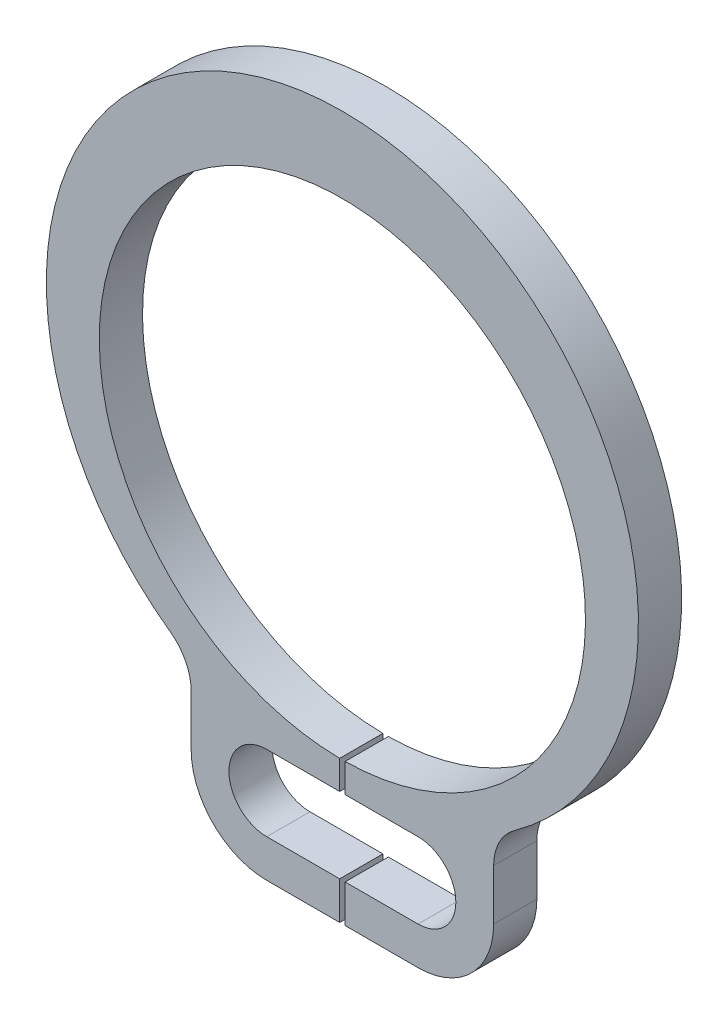
SolidWorks part; units mm, degrees
material "不锈钢 (铁素体)"
ref_plane "前视基准面" through (0, 0, 0) normal (0, 0, 1) x (1, 0, 0)
ref_plane "上视基准面" through (0, 0, 0) normal (0, 1, 0) x (1, 0, 0)
ref_plane "右视基准面" through (0, 0, 0) normal (1, 0, 0) x (0, 0, -1)
sketch "草图1" plane through (0, 0, 0) normal (0, 0, 1) x (1, 0, 0)
  line L0 (0, 1.0126) -> (0, -2.147) construction
  line L1 (-0.7, -3.5657) -> (0.7, -3.5657)
  line L2 (-1.4, -2.8657) -> (-1.4, -2.1453)
  line L3 (1.4, -2.8657) -> (1.4, -2.1453)
  circle A0 centre (0, 0) radius 2.25
  arc A1 (1.4, -2.1453) -> (-1.4, -2.1453) centre (0, 0.21) ccw
  circle A2 centre (-0.7, -2.8657) radius 0.35
  circle A4 centre (0.7, -2.8657) radius 0.35
  arc A5 (1.4, -2.8657) -> (0.7, -3.5657) centre (0.7, -2.8657) cw
  arc A6 (-1.4, -2.8657) -> (-0.7, -3.5657) centre (-0.7, -2.8657) ccw
  dimension "d3" = 4.5
  dimension "d0" = 0.7
  dimension "a" = 1.4
  dimension "b" = 0.7
  dimension "O1O2" = 0.21
  dimension "O3O4" = 1.4
extrude "凸台-拉伸1" add sketch "草图1" along normal blind 0.4
sketch "草图2" plane through (0, 0, 0.4) normal (0, 0, 1) x (1, 0, 0)
  line L0 (-0.7, -3.5657) -> (0.7, -3.5657) construction
  line L1 (-0.025, -3.5657) -> (0.025, -3.5657)
  line L2 (-0.025, -3.5657) -> (-0.025, 0)
  line L3 (-0.025, 0) -> (0.025, 0)
  line L4 (0.025, -3.5657) -> (0.025, 0)
  dimension "k" = 0.05
extrude "切除-拉伸1" cut sketch "草图2" against normal through all
fillet "圆角1" radius 0.4667 2 edges at (1.4, -2.1453, 0.2) (-1.4, -2.1453, 0.2)
sketch "草图3" plane through (0, 0, 0.4) normal (0, 0, 1) x (1, 0, 0)
  line L0 (-0.7, -2.8657) -> (0.7, -2.8657) construction
  line L1 (-0.7, -2.5157) -> (0.7, -2.5157)
  line L2 (-0.7, -3.2157) -> (0.7, -3.2157)
  arc A0 (-0.7, -2.5157) -> (-0.7, -3.2157) centre (-0.7, -2.8657) ccw
  arc A1 (0.7, -3.2157) -> (0.7, -2.5157) centre (0.7, -2.8657) ccw
  circle A2 centre (0.7, -2.8657) radius 0.35 construction
  point P4 (0, -2.8657)
extrude "切除-拉伸2" cut sketch "草图3" against normal through all
equation "\"D1@圆角1\" = \"a@草图1\" / 3"
